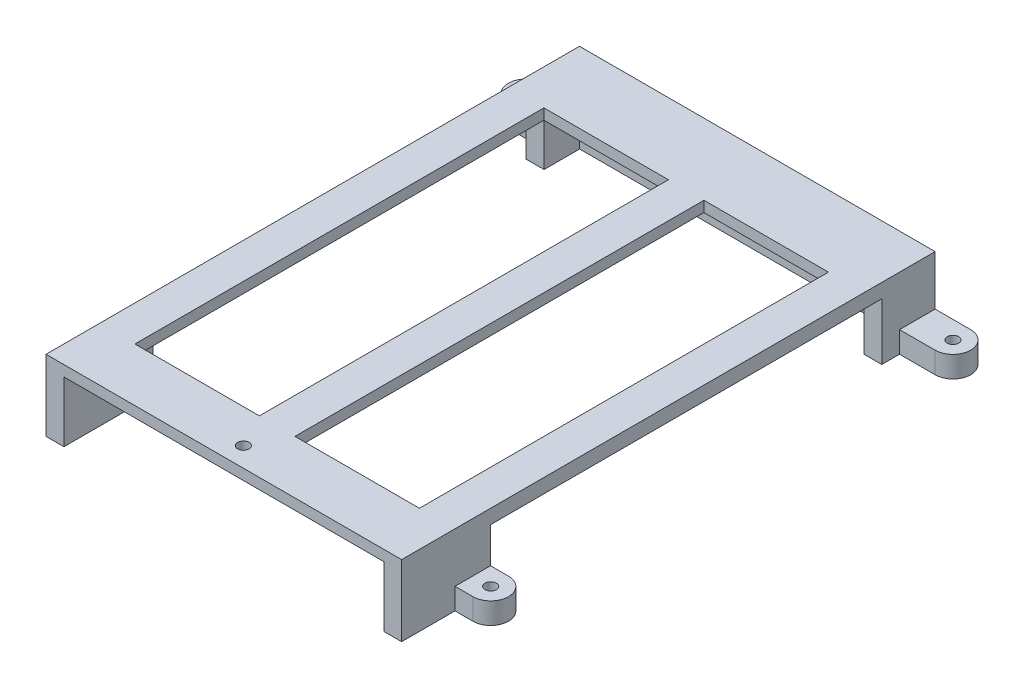
SolidWorks part; units mm, degrees
ref_plane "Front" through (0, 0, 0) normal (0, 0, 1) x (1, 0, 0)
ref_plane "Top" through (0, 0, 0) normal (0, 1, 0) x (1, 0, 0)
ref_plane "Right" through (0, 0, 0) normal (1, 0, 0) x (0, 0, -1)
sketch "草图2" plane through (0, 0, 0) normal (0, 0, 1) x (1, 0, 0)
  line L1 (-50, 20) -> (50, 20)
  line L2 (-50, 20) -> (-50, -20)
  line L3 (-50, -20) -> (50, -20)
  line L4 (50, 20) -> (50, -20)
  line L5 (-50, 20) -> (50, -20) construction
  line L6 (-50, -20) -> (50, 20) construction
  point P0 (0, 0)
  dimension "D1" = 100
  dimension "D2" = 40
extrude "凸台-拉伸1" add sketch "草图2" along normal blind 150
sketch "草图3" plane through (0, 0, 150) normal (0, 0, 1) x (1, 0, 0)
  line L0 (50, 20) -> (-50, 20) construction
  line L1 (-44.9554, 17) -> (45.0446, 17)
  line L2 (-44.9554, 17) -> (-44.9554, -15)
  line L3 (-44.9554, -15) -> (45.0446, -15)
  line L4 (45.0446, 17) -> (45.0446, -15)
  line L8 (-50, -20) -> (50, -20) construction
  point P0 (0, 0)
  dimension "D1" = 90
  dimension "D2" = 3
  dimension "D3" = 5
extrude "切除-拉伸1" cut sketch "草图3" against normal blind 145
sketch "草图4" plane through (0, -20, 0) normal (0, -1, 0) x (1, 0, 0)
  line L0 (-50, 150) -> (50, 150) construction
  line L1 (-40, 135) -> (-10, 135)
  line L2 (-40, 135) -> (-40, 20)
  line L3 (-40, 20) -> (-10, 20)
  line L4 (-10, 135) -> (-10, 20)
  line L5 (10, 135) -> (40, 135)
  line L6 (10, 135) -> (10, 20)
  line L7 (10, 20) -> (40, 20)
  line L8 (40, 135) -> (40, 20)
  line L9 (-50, 0) -> (50, 0) construction
  line L10 (-50, 150) -> (-50, 0) construction
  line L11 (50, 150) -> (50, 0) construction
  dimension "D1" = 15
  dimension "D2" = 20
  dimension "D3" = 20
  dimension "D4" = 15
  dimension "D5" = 10
  dimension "D6" = 10
  dimension "D7" = 30
  dimension "D8" = 30
extrude "切除-拉伸2" cut sketch "草图4" against normal blind 20
sketch "草图5" plane through (0, 20, 0) normal (0, 1, 0) x (1, 0, 0)
  line L0 (50, 0) -> (-50, 0) construction
  line L1 (-40, -20) -> (-5, -20)
  line L2 (-40, -20) -> (-40, -135)
  line L3 (-40, -135) -> (-5, -135)
  line L4 (-5, -20) -> (-5, -135)
  line L5 (5, -20) -> (40, -20)
  line L6 (5, -20) -> (5, -135)
  line L7 (5, -135) -> (40, -135)
  line L8 (40, -20) -> (40, -135)
  line L9 (-50, -150) -> (-50, 0) construction
  line L10 (50, -150) -> (50, 0) construction
  line L11 (50, -150) -> (-50, -150) construction
  dimension "D1" = 20
  dimension "D2" = 20
  dimension "D3" = 10
  dimension "D4" = 10
  dimension "D5" = 15
  dimension "D6" = 15
  dimension "D7" = 35
  dimension "D8" = 35
extrude "切除-拉伸3" cut sketch "草图5" against normal blind 20
sketch "草图6" plane through (-50, 0, 0) normal (-1, 0, 0) x (0, 0, 1)
  line L0 (150, 20) -> (0, 20) construction
  line L1 (15, 16) -> (135, 16)
  line L2 (15, 16) -> (15, -15)
  line L3 (15, -15) -> (135, -15)
  line L4 (135, 16) -> (135, -15)
  line L5 (150, -20) -> (0, -20) construction
  line L6 (150, 20) -> (150, -20) construction
  line L7 (0, 20) -> (0, -20) construction
  dimension "D1" = 4
  dimension "D2" = 5
  dimension "D3" = 15
  dimension "D4" = 15
extrude "切除-拉伸4" cut sketch "草图6" against normal blind 207
sketch "草图7" plane through (0, -20, 0) normal (0, -1, 0) x (1, 0, 0)
  line L1 (-10, 20) -> (-10, 135) construction
  line L2 (-50, 150) -> (50, 150) construction
  circle A0 centre (-5, 134) radius 1.5
  circle A1 centre (5, 134) radius 1.5
  circle A2 centre (5, 124) radius 1.5
  circle A3 centre (-5, 124) radius 1.5
  dimension "D1" = 3
  dimension "D2" = 3
  dimension "D3" = 3
  dimension "D4" = 3
  dimension "D5" = 10
  dimension "D6" = 10
  dimension "D7" = 10
  dimension "D8" = 5
  dimension "D9" = 5
  dimension "D10" = 16
  dimension "D11" = 16
  dimension "D12" = 10
extrude "切除-拉伸5" cut sketch "草图7" against normal blind 15
sketch "草图8" plane through (0, -20, 0) normal (0, -1, 0) x (1, 0, 0)
  circle A0 centre (0, 129) radius 2.5
  circle A1 centre (5, 134) radius 1.5 construction
  dimension "D1" = 5
  dimension "D2" = 5
extrude "切除-拉伸6" cut sketch "草图8" against normal blind 15
sketch "草图10" plane through (0, -20, 0) normal (0, -1, 0) x (1, 0, 0)
  line L1 (-10, 135) -> (-14, 135)
  line L2 (-10, 135) -> (-10, 117)
  line L3 (-10, 117) -> (-14, 117)
  line L4 (-14, 135) -> (-14, 117)
  line L5 (10, 135) -> (14, 135)
  line L6 (10, 135) -> (10, 117)
  line L7 (10, 117) -> (14, 117)
  line L8 (14, 135) -> (14, 117)
  dimension "D1" = 4
  dimension "D2" = 4
  dimension "D3" = 18
  dimension "D4" = 18
extrude "凸台-拉伸2" add sketch "草图10" against normal blind 5
sketch "草图11" plane through (0, -20, 0) normal (0, -1, 0) x (1, 0, 0)
  line L1 (-50, 150) -> (50, 150)
  line L2 (-50, 150) -> (-50, 0)
  line L3 (-50, 0) -> (50, 0)
  line L4 (50, 150) -> (50, 0)
extrude "切除-拉伸7" cut sketch "草图11" against normal blind 20
sketch "草图12" plane through (0, 0, 0) normal (0, -1, 0) x (1, 0, 0)
  line L0 (-44.9554, 135) -> (-54.9554, 135)
  line L4 (-44.9554, 135) -> (-44.9554, 125)
  line L8 (-44.9554, 125) -> (-54.9554, 125)
  line L9 (50, 0) -> (60, 0)
  line L10 (50, 0) -> (50, 10)
  line L11 (50, 10) -> (60, 10)
  line L12 (45.0446, 135) -> (55.0446, 135)
  line L13 (-50, 0) -> (-60, 0)
  line L14 (-50, 0) -> (-50, 10)
  line L15 (-50, 10) -> (-60, 10)
  line L16 (45.0446, 135) -> (45.0446, 125)
  line L17 (45.0446, 125) -> (55.0446, 125)
  arc A0 (-60, 10) -> (-60, 0) centre (-60, 5) ccw
  arc A1 (60, 0) -> (60, 10) centre (60, 5) ccw
  circle A4 centre (-60, 5) radius 1.6
  circle A5 centre (60, 5) radius 1.6
  arc A8 (-54.9554, 135) -> (-54.9554, 125) centre (-54.9554, 130) ccw
  circle A9 centre (-54.9554, 130) radius 1.6
  arc A10 (55.0446, 125) -> (55.0446, 135) centre (55.0446, 130) ccw
  circle A11 centre (55.0446, 130) radius 1.6
extrude "凸台-拉伸5" add sketch "草图12" against normal blind 6
sketch "草图13" plane through (0, 6, 0) normal (0, 1, 0) x (1, 0, 0)
  line L1 (50, -135) -> (45.0446, -135)
  line L2 (50, -135) -> (50, -125)
  line L3 (50, -125) -> (45.0446, -125)
  line L4 (45.0446, -135) -> (45.0446, -125)
  line L5 (-50, -135) -> (-44.9554, -135)
  line L6 (-50, -135) -> (-50, -125)
  line L7 (-50, -125) -> (-44.9554, -125)
  line L8 (-44.9554, -135) -> (-44.9554, -125)
extrude "凸台-拉伸6" add sketch "草图13" along normal up to next
sketch "草图14" plane through (0, 20, 0) normal (0, 1, 0) x (1, 0, 0)
  line L0 (50, -150) -> (-50, -150) construction
  circle A0 centre (0, -144.5) radius 1.6
  dimension "D1" = 3.2
  dimension "D2" = 5.5
extrude "切除-拉伸8" cut sketch "草图14" against normal blind 10
